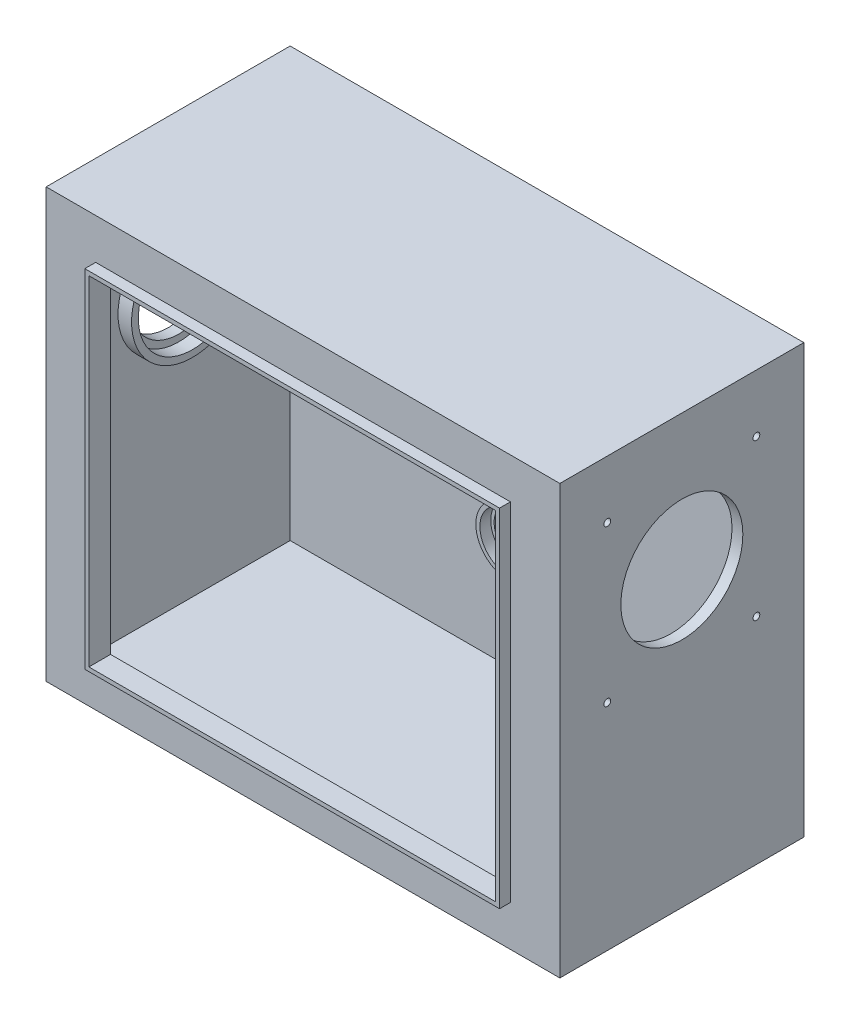
SolidWorks part; units mm, degrees
ref_plane "Alzado" through (0, 0, 0) normal (0, 0, 1) x (1, 0, 0)
ref_plane "Planta" through (0, 0, 0) normal (0, 1, 0) x (1, 0, 0)
ref_plane "Vista lateral" through (0, 0, 0) normal (1, 0, 0) x (0, 0, -1)
sketch "Croquis1" plane through (0, 0, 0) normal (0, 0, 1) x (1, 0, 0)
  line L0 (-189.5, 158) -> (189.5, 158)
  line L1 (-181.5, -150) -> (181.5, -150) construction
  line L2 (-181.5, -150) -> (-181.5, 150) construction
  line L3 (-181.5, 150) -> (181.5, 150) construction
  line L4 (181.5, -150) -> (181.5, 150) construction
  line L5 (-181.5, -150) -> (181.5, 150) construction
  line L6 (-181.5, 150) -> (181.5, -150) construction
  line L7 (189.5, -158) -> (189.5, 158)
  line L8 (-189.5, -158) -> (189.5, -158)
  line L9 (-189.5, -158) -> (-189.5, 158)
  point P0 (0, 0)
  dimension "D1" = 363
  dimension "D2" = 300
  dimension "D3" = 8
extrude "Saliente-Extruir1" add sketch "Croquis1" along normal blind 180
shell "Vaciado1" thickness 8
sketch "Croquis2" plane through (-189.5, 0, 0) normal (-1, 0, 0) x (0, 0, 1)
  line L0 (0, 158) -> (90, 158) construction
  line L1 (180, 158) -> (0, 158) construction
  circle A0 centre (90, 58) radius 35
extrude "Cortar-Extruir4" cut sketch "Croquis2" against normal blind 20 contours A0
sketch "Croquis4" plane through (-181.5, 0, 0) normal (1, 0, 0) x (0, 0, -1)
  circle A1 centre (-90, 58) radius 40
  circle A2 centre (-90, 58) radius 45
extrude "Saliente-Extruir4" add sketch "Croquis4" along normal blind 10
sketch "Croquis6" plane through (189.5, 0, 0) normal (1, 0, 0) x (0, 0, -1)
  line L0 (-90, 158) -> (-90, 58) construction
  line L1 (-180, 158) -> (0, 158) construction
  circle A0 centre (-90, 58) radius 45
  dimension "D1" = 90
extrude "Cortar-Extruir6" cut sketch "Croquis6" against normal blind 10 contours A0
sketch "Croquis7" plane through (0, 0, 8) normal (0, 0, 1) x (1, 0, 0)
  circle A3 centre (-2.5, -53) radius 21
  circle A4 centre (-2.5, -53) radius 24
  dimension "D1" = 42
  dimension "D2" = 48
extrude "Saliente-Extruir9" add sketch "Croquis7" along normal blind 18
ref_plane "Plano6" through (0, 0, 180) normal (0, 0, 1) x (1, 0, 0)
sketch "Croquis11" plane through (0, 0, 180) normal (0, 0, 1) x (1, 0, 0)
  line L1 (181.5, 150) -> (-181.5, 150)
  line L2 (181.5, 150) -> (181.5, -150)
  line L3 (181.5, -150) -> (-181.5, -150)
  line L4 (-181.5, 150) -> (-181.5, -150)
  line L5 (181.5, 150) -> (-181.5, -150) construction
  line L6 (181.5, -150) -> (-181.5, 150) construction
  line L7 (-150, 125) -> (150, 125)
  line L8 (-150, 125) -> (-150, -125)
  line L9 (-150, -125) -> (150, -125)
  line L10 (150, 125) -> (150, -125)
  line L11 (-150, 125) -> (150, -125) construction
  line L12 (-150, -125) -> (150, 125) construction
  point P0 (0, 0)
  point P7 (0, 0)
  dimension "D1" = 300
  dimension "D2" = 250
extrude "Saliente-Extruir10" add sketch "Croquis11" against normal blind 8
sketch "Croquis12" plane through (0, 0, 180) normal (0, 0, 1) x (1, 0, 0)
  line L1 (150, -125) -> (-150, -125)
  line L2 (150, -125) -> (150, 125)
  line L3 (150, 125) -> (-150, 125)
  line L4 (-150, -125) -> (-150, 125)
  line L5 (150, -125) -> (-150, 125) construction
  line L6 (150, 125) -> (-150, -125) construction
  line L7 (153, -128) -> (-153, -128)
  line L8 (153, -128) -> (153, 128)
  line L9 (153, 128) -> (-153, 128)
  line L10 (-153, -128) -> (-153, 128)
  line L11 (153, -128) -> (-153, 128) construction
  line L12 (153, 128) -> (-153, -128) construction
  point P0 (0, 0)
  point P8 (0, 0)
  dimension "D1" = 3
  dimension "D2" = 3
extrude "Saliente-Extruir11" add sketch "Croquis12" along normal blind 8
sketch "Croquis20" plane through (0, 0, 8) normal (0, 0, 1) x (1, 0, 0)
  circle A0 centre (-2.5, -53) radius 18.5
  circle A1 centre (-2.5, -53) radius 21
  circle A2 centre (-2.5, -53) radius 21 construction
  dimension "D1" = 37
extrude "Saliente-Extruir19" add sketch "Croquis20" along normal blind 10
hole_wizard "Taladro roscado M63" positions "Croquis3D6" profile "Croquis26" tap size "M6" standard "DIN" end condition through all
sketch3d "Croquis3D6"
  line L2 (-189.5, 0.5, 145) -> (-189.5, 115.5, 145) construction
  line L3 (-189.5, 0.5, 145) -> (-189.5, 0.5, 35) construction
  line L4 (-189.5, 0.5, 35) -> (-189.5, 115.5, 35) construction
  line L5 (-189.5, 115.5, 145) -> (-189.5, 115.5, 35) construction
  line L6 (-189.5, 0.5, 145) -> (-189.5, 115.5, 35) construction
  line L7 (-189.5, 0.5, 35) -> (-189.5, 115.5, 145) construction
  circle A1 centre (-189.5, 58, 90) radius 35 construction
  point P0 (-189.5, 115.5, 35)
  point P2 (-189.5, 115.5, 145)
  point P4 (-189.5, 0.5, 145)
  point P6 (-189.5, 0.5, 35)
  point P265 (-189.5, 58, 90)
  point P268 (-224.5, 58, 90)
  dimension "D1" = 115
  dimension "D2" = 0
  dimension "D3" = 110
sketch "Croquis26" plane through (-189.5, 115.5, 35) normal (0, 1, 0) x (0, 0, 1)
  line L0 (0, 0) -> (0, 379)
  line L1 (0, 379) -> (2.5, 379)
  line L2 (2.5, 379) -> (2.5, 0)
  line L5 (2.5, 0) -> (0, 0)
  line L11 (0, -6.35) -> (0, 107.95) construction
  dimension "Diámetro de perforador para roscar hasta el siguiente" = 5
  dimension "Profundidad de perforador para roscar hasta el siguiente" = 379
cosmetic thread "Rosca de taladro1" parameters "D2"=6
cosmetic thread "Rosca de taladro2" parameters "D2"=6
cosmetic thread "Rosca de taladro3" parameters "D2"=6
cosmetic thread "Rosca de taladro4" parameters "D2"=6
sketch "Croquis27" plane through (0, 0, 0) normal (0, 0, -1) x (-1, 0, 0)
  circle A0 centre (2.5, -53) radius 11
  circle A1 centre (2.5, -53) radius 21 construction
  dimension "D1" = 22
